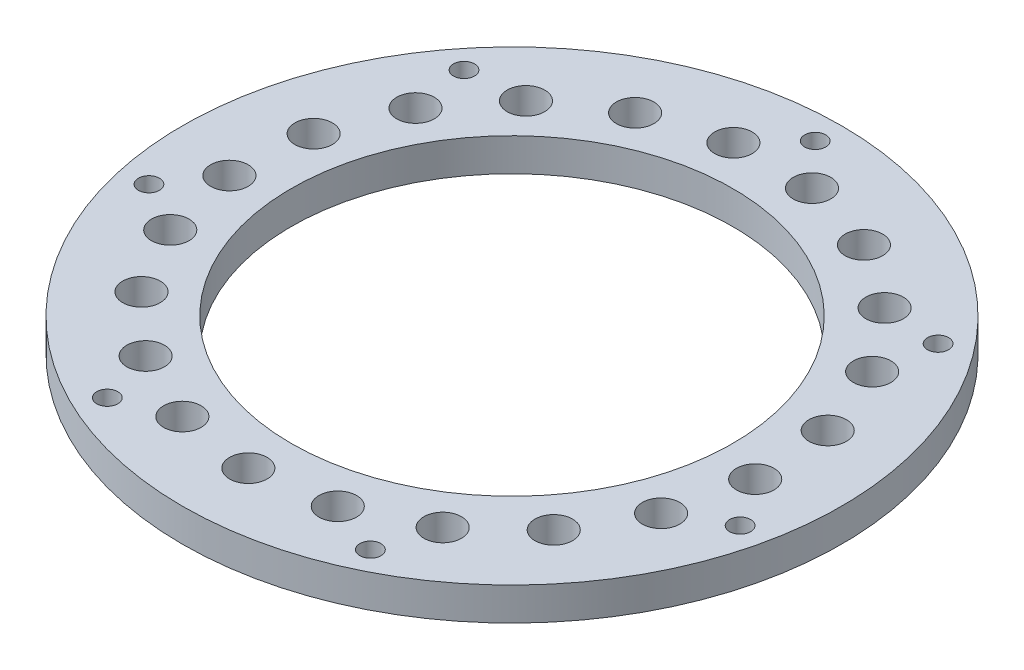
SolidWorks part; units mm, degrees
ref_plane "Ebene vorne" through (0, 0, 0) normal (0, 0, 1) x (1, 0, 0)
ref_plane "Ebene oben" through (0, 0, 0) normal (0, 1, 0) x (1, 0, 0)
ref_plane "Ebene rechts" through (0, 0, 0) normal (1, 0, 0) x (0, 0, -1)
sketch "Skizze1" plane through (0, 0, 0) normal (0, 1, 0) x (1, 0, 0)
  circle A0 centre (0, 0) radius 33.5
  circle A1 centre (0, 0) radius 50
  dimension "D1" = 67
  dimension "D2" = 100
extrude "Aufsatz-Linear austragen1" add sketch "Skizze1" along normal blind 5
hole_wizard "Ø3.2 (3.2) Durchmesser Bohrung2" positions "Skizze6" profile "Skizze7" hole size "Ø3.2" standard "DIN" end condition through all
sketch "Skizze6" plane through (0, 5, 0) normal (0, 1, 0) x (1, 0, 0)
  line L0 (0, 0) -> (0, 50000) construction
  circle A0 centre (0, 0) radius 46 construction
  point P9 (0, 46)
  dimension "D1" = 92
sketch "Skizze7" plane through (0, 5, -46) normal (1, 0, 0) x (0, 0, 1)
  line L0 (0, 0) -> (0, 5)
  line L1 (0, 5) -> (1.6, 5)
  line L2 (1.6, 5) -> (1.6, 0)
  line L5 (1.6, 0) -> (0, 0)
  line L11 (0, -6.35) -> (0, 107.95) construction
  dimension "Bohrerdurchmesser" = 3.2
  dimension "Bohrungstiefe" = 5
pattern_circular "Kreismuster1" count 7 over 360 about axis through (0, 0, 0) along (0, 1, 0) of "Ø3.2 (3.2) Durchmesser Bohrung2"
hole_wizard "Ø5.6 (5.6) Durchmesser Bohrung2" positions "Skizze8" profile "Skizze9" hole size "Ø5.6" standard "DIN" end condition through all
sketch "Skizze8" plane through (0, 5, 0) normal (0, 1, 0) x (1, 0, 0)
  line L1 (0, 0) -> (0, 50000) construction
  circle A0 centre (0, 0) radius 40 construction
  point P10 (0, -40)
  dimension "D1" = 80
sketch "Skizze9" plane through (0, 5, 40) normal (1, 0, 0) x (0, 0, 1)
  line L0 (0, 0) -> (0, 5)
  line L1 (0, 5) -> (2.85, 5)
  line L2 (2.85, 5) -> (2.85, 0)
  line L5 (2.85, 0) -> (0, 0)
  line L11 (0, -6.35) -> (0, 107.95) construction
  dimension "Bohrerdurchmesser" = 5.7
  dimension "Bohrungstiefe" = 5
pattern_circular "Kreismuster2" count 21 over 360 about axis through (0, 0, 0) along (0, 1, 0) of "Ø5.6 (5.6) Durchmesser Bohrung2"
